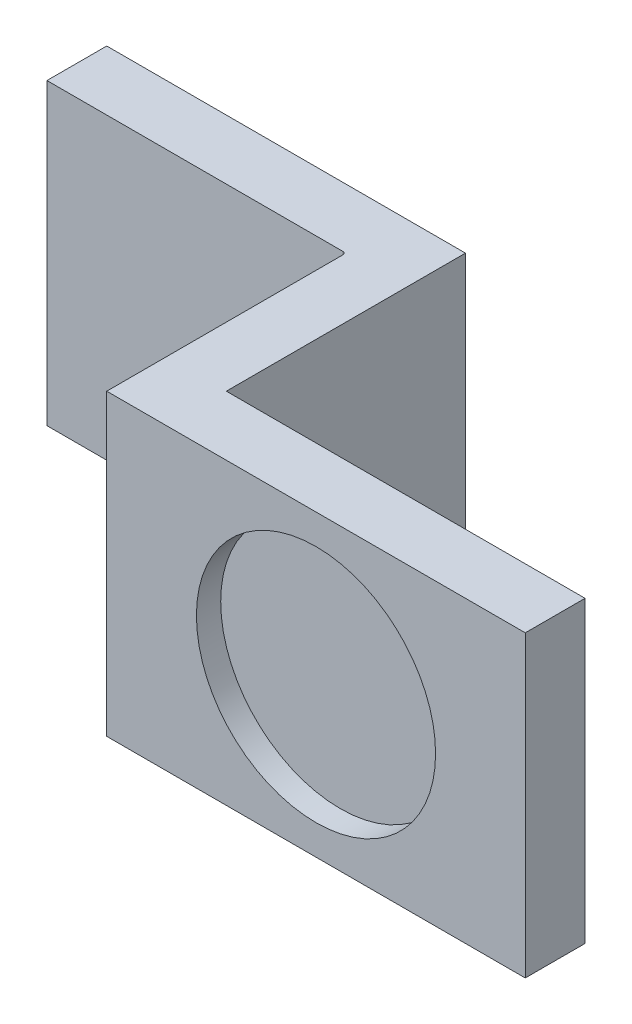
SolidWorks part; units mm, degrees
ref_plane "Plan de face" through (0, 0, 0) normal (0, 0, 1) x (1, 0, 0)
ref_plane "Plan de dessus" through (0, 0, 0) normal (0, 1, 0) x (1, 0, 0)
ref_plane "Plan de droite" through (0, 0, 0) normal (1, 0, 0) x (0, 0, -1)
sketch "Esquisse1" plane through (0, 0, 0) normal (0, 0, 1) x (1, 0, 0)
  line L1 (-15, 12.5) -> (15, 12.5)
  line L2 (-15, 12.5) -> (-15, -12.5)
  line L3 (-15, -12.5) -> (15, -12.5)
  line L4 (15, 12.5) -> (15, -12.5)
  line L5 (-15, 12.5) -> (15, -12.5) construction
  line L6 (-15, -12.5) -> (15, 12.5) construction
  point P0 (0, 0)
  dimension "D1" = 30
  dimension "D2" = 25
extrude "Boss.-Extru.2" add sketch "Esquisse1" along normal blind 5
sketch "Esquisse2" plane through (15, 0, 0) normal (1, 0, 0) x (0, 0, -1)
  line L0 (-14.994, 0) -> (0, 0) construction
  line L4 (0, -12.5) -> (0, 12.5)
  line L5 (0, 12.5) -> (-5, 12.5)
  line L6 (-5, 12.5) -> (-5, -12.5)
  line L7 (-5, -12.5) -> (0, -12.5)
  line L8 (0, -12.5) -> (0, 12.5)
  line L9 (0, 12.5) -> (-3.2003, 12.5)
  line L11 (-5, -12.5) -> (0, -12.5)
  line L14 (-25, 12.5) -> (-5, 12.5)
  line L15 (-25, 12.5) -> (-25, -12.5)
  line L16 (-25, -12.5) -> (-5, -12.5)
  line L17 (-5, 12.5) -> (-5, -12.5)
  line L18 (-25, 12.5) -> (-5, -12.5) construction
  line L19 (-25, -12.5) -> (-5, 12.5) construction
  point P8 (-15, 0)
  line M11 (-5, 12.5) -> (-5, -12.5)
  dimension "D2" = 20
  dimension "D1" = 0
extrude "Boss.-Extru.4" add sketch "Esquisse2" against normal blind 5 contours L15 L16 L14 M11
sketch "Esquisse3" plane through (15, 0, 0) normal (1, 0, 0) x (0, 0, -1)
  line L0 (-25, 12.5) -> (0, 12.5) construction
  line L1 (-20, 12.5) -> (-25, 12.5)
  line L2 (-20, 12.5) -> (-20, -12.5)
  line L3 (-20, -12.5) -> (-25, -12.5)
  line L4 (-25, 12.5) -> (-25, -12.5)
  line L5 (-20, 12.5) -> (-25, -12.5) construction
  line L7 (-20, -12.5) -> (-25, 12.5) construction
  point P0 (-22.5, 0)
  dimension "D1" = 5
extrude "Boss.-Extru.5" add sketch "Esquisse3" along normal blind 30
fillet "Congé1" radius 0.25 1 edges at (10, 0, 5)
sketch "Esquisse4" plane through (0, 0, 25) normal (0, 0, 1) x (1, 0, 0)
  circle A0 centre (27.5, 0) radius 10
  dimension "D1" = 20
extrude "Enlèv. mat.-Extru.1" cut sketch "Esquisse4" against normal blind 2.03
